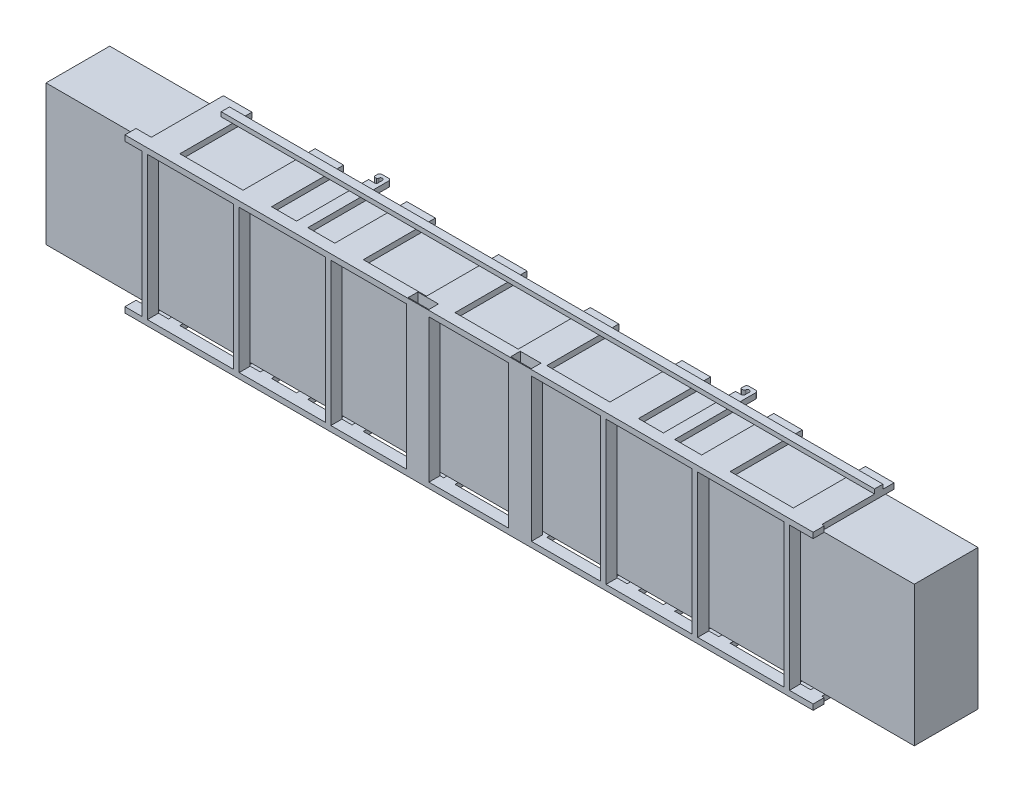
SolidWorks part; units mm, degrees
ref_plane "Front Plane" through (0, 0, 0) normal (0, 0, 1) x (1, 0, 0)
ref_plane "Top Plane" through (0, 0, 0) normal (0, 1, 0) x (1, 0, 0)
ref_plane "Right Plane" through (0, 0, 0) normal (1, 0, 0) x (0, 0, -1)
sketch "Sketch1" plane through (0, 0, 0) normal (0, 0, 1) x (1, 0, 0)
  line L0 (0, 1388) -> (6190, 1388)
  line L1 (0, 50) -> (6190, 50)
  line L2 (0, 50) -> (0, 0)
  line L3 (0, 0) -> (6190, 0)
  line L4 (6190, 50) -> (6190, 0)
  line L5 (0, 1388) -> (0, 1338)
  line L6 (0, 1338) -> (6190, 1338)
  line L7 (6190, 1388) -> (6190, 1338)
  dimension "D1" = 1288
  dimension "D2" = 50
extrude "Boss-Extrude1" add sketch "Sketch1" along normal blind 100
sketch "Sketch2" plane through (0, 0, 0) normal (0, -1, 0) x (1, 0, 0)
  line L0 (0, 100) -> (6190, 100) construction
  line L1 (2534, 100) -> (2734, 100)
  line L2 (2534, 100) -> (2534, 0)
  line L3 (2534, 0) -> (2734, 0)
  line L4 (2734, 100) -> (2734, 0)
  line L5 (0, 0) -> (6190, 0) construction
  line L6 (0, 100) -> (0, 0) construction
  line L8 (3456, 100) -> (3656, 100)
  line L9 (3456, 100) -> (3456, 0)
  line L10 (3456, 0) -> (3656, 0)
  line L11 (3656, 100) -> (3656, 0)
  point P8 (0, 50)
  dimension "D1" = 200
  dimension "D2" = 2534
  dimension "D3" = 2534
  dimension "D4" = 200
extrude "Boss-Extrude2" add sketch "Sketch2" against normal up to surface (1388 mm away) up to face at (3095, 1388, 50)
sketch "Sketch3" plane through (0, 1388, 0) normal (0, 1, 0) x (1, 0, 0)
  line L2 (0, -100) -> (0, 0) construction
  line L3 (6190, -100) -> (6190, 0) construction
  line L12 (2541, -7) -> (2727, -7)
  line L13 (2727, -7) -> (2727, -93)
  line L14 (2541, -93) -> (2727, -93)
  line L15 (2541, -7) -> (2541, -93)
  line L16 (3463, -7) -> (3649, -7)
  line L17 (3649, -7) -> (3649, -93)
  line L18 (3463, -93) -> (3649, -93)
  line L19 (3463, -7) -> (3463, -93)
  point P2 (6190, -50)
  dimension "D1" = 186
  dimension "D2" = 186
  dimension "D3" = 2541
  dimension "D4" = 2541
extrude "Cut-Extrude1" cut sketch "Sketch3" against normal through all
sketch "Sketch4" plane through (0, 50, 0) normal (0, 1, 0) x (1, 0, 0)
  line L0 (2534, 0) -> (0, 0) construction
  line L1 (152, 0) -> (202, 0)
  line L2 (152, 0) -> (152, -100)
  line L3 (152, -100) -> (202, -100)
  line L4 (202, 0) -> (202, -100)
  line L5 (2534, -100) -> (0, -100) construction
  line L6 (0, -100) -> (0, 0) construction
  line L7 (977, 0) -> (977, -100)
  line L8 (977, 0) -> (1027, 0)
  line L9 (1027, 0) -> (1027, -100)
  line L10 (977, -100) -> (1027, -100)
  line L11 (1802, 0) -> (1802, -100)
  line L12 (1802, 0) -> (1852, 0)
  line L13 (1852, 0) -> (1852, -100)
  line L14 (1802, -100) -> (1852, -100)
  line L15 (2627, 0) -> (2627, -100)
  line L16 (2627, 0) -> (2677, 0)
  line L17 (2677, 0) -> (2677, -100)
  line L18 (2627, -100) -> (2677, -100)
  line L19 (3452, 0) -> (3452, -100)
  line L20 (3452, 0) -> (3502, 0)
  line L21 (3502, 0) -> (3502, -100)
  line L22 (3452, -100) -> (3502, -100)
  line L23 (4277, 0) -> (4277, -100)
  line L24 (4277, 0) -> (4327, 0)
  line L25 (4327, 0) -> (4327, -100)
  line L26 (4277, -100) -> (4327, -100)
  line L27 (5102, 0) -> (5102, -100)
  line L28 (5102, 0) -> (5152, 0)
  line L29 (5152, 0) -> (5152, -100)
  line L30 (5102, -100) -> (5152, -100)
  line L31 (5927, 0) -> (5927, -100)
  line L32 (5927, 0) -> (5977, 0)
  line L33 (5977, 0) -> (5977, -100)
  line L34 (5927, -100) -> (5977, -100)
  dimension "D1" = 152
  dimension "D2" = 50
  dimension "D3" = 8
extrude "Boss-Extrude3" add sketch "Sketch4" along normal up to next
sketch "Sketch5" plane through (0, 0, 0) normal (0, 0, 1) x (1, 0, 0)
  line L0 (137.4, 1388) -> (137.4, 1338)
  line L1 (140.4, 1385.8) -> (140.4, 1338)
  line L2 (292.4, 1385.8) -> (140.4, 1385.8)
  line L3 (394, 1388) -> (394, 1338)
  line L4 (137.4, 1388) -> (394, 1388)
  line L5 (394, 1338) -> (292.4, 1338)
  line L6 (140.4, 1338) -> (137.4, 1338)
  line L7 (292.4, 1385.8) -> (292.4, 1338)
  line L8 (152, 1338) -> (137.4, 1338) construction
  line L9 (0, 1338) -> (152, 1338) construction
  line L10 (962.4, 1388) -> (962.4, 1338)
  line L11 (965.4, 1385.8) -> (965.4, 1338)
  line L12 (1117.4, 1385.8) -> (965.4, 1385.8)
  line L13 (1219, 1388) -> (1219, 1338)
  line L14 (962.4, 1388) -> (1219, 1388)
  line L15 (1219, 1338) -> (1117.4, 1338)
  line L16 (965.4, 1338) -> (962.4, 1338)
  line L17 (1117.4, 1385.8) -> (1117.4, 1338)
  line L18 (977, 1338) -> (962.4, 1338) construction
  line L19 (1787.4, 1388) -> (1787.4, 1338)
  line L20 (1790.4, 1385.8) -> (1790.4, 1338)
  line L21 (1942.4, 1385.8) -> (1790.4, 1385.8)
  line L22 (2044, 1388) -> (2044, 1338)
  line L23 (1787.4, 1388) -> (2044, 1388)
  line L24 (2044, 1338) -> (1942.4, 1338)
  line L25 (1790.4, 1338) -> (1787.4, 1338)
  line L26 (1942.4, 1385.8) -> (1942.4, 1338)
  line L27 (1802, 1338) -> (1787.4, 1338) construction
  line L28 (2612.4, 1388) -> (2612.4, 1338)
  line L29 (2615.4, 1385.8) -> (2615.4, 1338)
  line L30 (2767.4, 1385.8) -> (2615.4, 1385.8)
  line L31 (2869, 1388) -> (2869, 1338)
  line L32 (2612.4, 1388) -> (2869, 1388)
  line L33 (2869, 1338) -> (2767.4, 1338)
  line L34 (2615.4, 1338) -> (2612.4, 1338)
  line L35 (2767.4, 1385.8) -> (2767.4, 1338)
  line L36 (2627, 1338) -> (2612.4, 1338) construction
  line L37 (3437.4, 1388) -> (3437.4, 1338)
  line L38 (3440.4, 1385.8) -> (3440.4, 1338)
  line L39 (3592.4, 1385.8) -> (3440.4, 1385.8)
  line L40 (3694, 1388) -> (3694, 1338)
  line L41 (3437.4, 1388) -> (3694, 1388)
  line L42 (3694, 1338) -> (3592.4, 1338)
  line L43 (3440.4, 1338) -> (3437.4, 1338)
  line L44 (3592.4, 1385.8) -> (3592.4, 1338)
  line L45 (3452, 1338) -> (3437.4, 1338) construction
  line L46 (4262.4, 1388) -> (4262.4, 1338)
  line L47 (4265.4, 1385.8) -> (4265.4, 1338)
  line L48 (4417.4, 1385.8) -> (4265.4, 1385.8)
  line L49 (4519, 1388) -> (4519, 1338)
  line L50 (4262.4, 1388) -> (4519, 1388)
  line L51 (4519, 1338) -> (4417.4, 1338)
  line L52 (4265.4, 1338) -> (4262.4, 1338)
  line L53 (4417.4, 1385.8) -> (4417.4, 1338)
  line L54 (4277, 1338) -> (4262.4, 1338) construction
  line L55 (5087.4, 1388) -> (5087.4, 1338)
  line L56 (5090.4, 1385.8) -> (5090.4, 1338)
  line L57 (5242.4, 1385.8) -> (5090.4, 1385.8)
  line L58 (5344, 1388) -> (5344, 1338)
  line L59 (5087.4, 1388) -> (5344, 1388)
  line L60 (5344, 1338) -> (5242.4, 1338)
  line L61 (5090.4, 1338) -> (5087.4, 1338)
  line L62 (5242.4, 1385.8) -> (5242.4, 1338)
  line L63 (5102, 1338) -> (5087.4, 1338) construction
  line L64 (5912.4, 1388) -> (5912.4, 1338)
  line L65 (5915.4, 1385.8) -> (5915.4, 1338)
  line L66 (6067.4, 1385.8) -> (5915.4, 1385.8)
  line L67 (6169, 1388) -> (6169, 1338)
  line L68 (5912.4, 1388) -> (6169, 1388)
  line L69 (6169, 1338) -> (6067.4, 1338)
  line L70 (5915.4, 1338) -> (5912.4, 1338)
  line L71 (6067.4, 1385.8) -> (6067.4, 1338)
  line L72 (5927, 1338) -> (5912.4, 1338) construction
  line L73 (152, 694) -> (5977, 694) construction
  line L74 (152, 1338) -> (152, 50) construction
  line L75 (5977, 1338) -> (5977, 50) construction
  line L76 (5927, 50) -> (5912.4, 50) construction
  line L77 (5102, 50) -> (5087.4, 50) construction
  line L78 (4277, 50) -> (4262.4, 50) construction
  line L79 (3452, 50) -> (3437.4, 50) construction
  line L80 (2627, 50) -> (2612.4, 50) construction
  line L81 (1802, 50) -> (1787.4, 50) construction
  line L82 (977, 50) -> (962.4, 50) construction
  line L83 (152, 50) -> (137.4, 50) construction
  line L84 (6067.4, 2.2) -> (6067.4, 50)
  line L85 (5915.4, 50) -> (5912.4, 50)
  line L86 (6169, 50) -> (6067.4, 50)
  line L87 (5912.4, 0) -> (6169, 0)
  line L88 (6169, 0) -> (6169, 50)
  line L89 (6067.4, 2.2) -> (5915.4, 2.2)
  line L90 (5915.4, 2.2) -> (5915.4, 50)
  line L91 (5912.4, 0) -> (5912.4, 50)
  line L92 (5242.4, 2.2) -> (5242.4, 50)
  line L93 (5090.4, 50) -> (5087.4, 50)
  line L94 (5344, 50) -> (5242.4, 50)
  line L95 (5087.4, 0) -> (5344, 0)
  line L96 (5344, 0) -> (5344, 50)
  line L97 (5242.4, 2.2) -> (5090.4, 2.2)
  line L98 (5090.4, 2.2) -> (5090.4, 50)
  line L99 (5087.4, 0) -> (5087.4, 50)
  line L100 (4417.4, 2.2) -> (4417.4, 50)
  line L101 (4265.4, 50) -> (4262.4, 50)
  line L102 (4519, 50) -> (4417.4, 50)
  line L103 (4262.4, 0) -> (4519, 0)
  line L104 (4519, 0) -> (4519, 50)
  line L105 (4417.4, 2.2) -> (4265.4, 2.2)
  line L106 (4265.4, 2.2) -> (4265.4, 50)
  line L107 (4262.4, 0) -> (4262.4, 50)
  line L108 (3592.4, 2.2) -> (3592.4, 50)
  line L109 (3440.4, 50) -> (3437.4, 50)
  line L110 (3694, 50) -> (3592.4, 50)
  line L111 (3437.4, 0) -> (3694, 0)
  line L112 (3694, 0) -> (3694, 50)
  line L113 (3592.4, 2.2) -> (3440.4, 2.2)
  line L114 (3440.4, 2.2) -> (3440.4, 50)
  line L115 (3437.4, 0) -> (3437.4, 50)
  line L116 (2767.4, 2.2) -> (2767.4, 50)
  line L117 (2615.4, 50) -> (2612.4, 50)
  line L118 (2869, 50) -> (2767.4, 50)
  line L119 (2612.4, 0) -> (2869, 0)
  line L120 (2869, 0) -> (2869, 50)
  line L121 (2767.4, 2.2) -> (2615.4, 2.2)
  line L122 (2615.4, 2.2) -> (2615.4, 50)
  line L123 (2612.4, 0) -> (2612.4, 50)
  line L124 (1942.4, 2.2) -> (1942.4, 50)
  line L125 (1790.4, 50) -> (1787.4, 50)
  line L126 (2044, 50) -> (1942.4, 50)
  line L127 (1787.4, 0) -> (2044, 0)
  line L128 (2044, 0) -> (2044, 50)
  line L129 (1942.4, 2.2) -> (1790.4, 2.2)
  line L130 (1790.4, 2.2) -> (1790.4, 50)
  line L131 (1787.4, 0) -> (1787.4, 50)
  line L132 (1117.4, 2.2) -> (1117.4, 50)
  line L133 (965.4, 50) -> (962.4, 50)
  line L134 (1219, 50) -> (1117.4, 50)
  line L135 (962.4, 0) -> (1219, 0)
  line L136 (1219, 0) -> (1219, 50)
  line L137 (1117.4, 2.2) -> (965.4, 2.2)
  line L138 (965.4, 2.2) -> (965.4, 50)
  line L139 (962.4, 0) -> (962.4, 50)
  line L140 (292.4, 2.2) -> (292.4, 50)
  line L141 (140.4, 50) -> (137.4, 50)
  line L142 (394, 50) -> (292.4, 50)
  line L143 (137.4, 0) -> (394, 0)
  line L144 (394, 0) -> (394, 50)
  line L145 (292.4, 2.2) -> (140.4, 2.2)
  line L146 (140.4, 2.2) -> (140.4, 50)
  line L147 (137.4, 0) -> (137.4, 50)
  dimension "D1" = 50
  dimension "D2" = 50
  dimension "D3" = 8
extrude "Boss-Extrude4" add sketch "Sketch5" against normal blind 648.4
sketch "Sketch8" plane through (0, 50, 0) normal (0, 1, 0) x (1, 0, 0)
  line L0 (1443.4, 648.4) -> (1497.5, 648.4)
  line L1 (1453.4, 693.4) -> (1467.5, 693.4)
  line L2 (1443.4, 728.4) -> (1443.4, 703.4)
  line L3 (1512.5, 703.4) -> (1512.5, 663.4)
  line L4 (1545, 0) -> (1443.4, 0)
  line L5 (1443.4, 0) -> (1443.4, 648.4)
  line L6 (1545, 0) -> (1545, 728.4)
  line L7 (1463.4, 748.4) -> (1525, 748.4)
  line L8 (0, 0) -> (1443.4, 0) construction
  line L9 (6190, 0) -> (4845, 0) construction
  line L10 (4845, 0) -> (4743.4, 0)
  line L11 (4812.5, 703.4) -> (4812.5, 663.4)
  line L12 (4743.4, 728.4) -> (4743.4, 703.4)
  line L13 (4753.4, 693.4) -> (4767.5, 693.4)
  line L14 (4743.4, 0) -> (4743.4, 648.4)
  line L15 (4845, 0) -> (4845, 728.4)
  line L16 (4743.4, 648.4) -> (4797.5, 648.4)
  line L17 (4763.4, 748.4) -> (4825, 748.4)
  arc A0 (1497.5, 648.4) -> (1512.5, 663.4) centre (1497.5, 663.4) ccw
  arc A1 (1443.4, 703.4) -> (1453.4, 693.4) centre (1453.4, 703.4) ccw
  arc A2 (1463.4, 748.4) -> (1443.4, 728.4) centre (1463.4, 728.4) ccw
  arc A3 (1545, 728.4) -> (1525, 748.4) centre (1525, 728.4) ccw
  arc A4 (1512.5, 703.4) -> (1477.5, 703.4) centre (1495, 703.4) ccw
  arc A5 (1467.5, 693.4) -> (1477.5, 703.4) centre (1467.5, 703.4) ccw
  arc A6 (4845, 728.4) -> (4825, 748.4) centre (4825, 728.4) ccw
  arc A7 (4763.4, 748.4) -> (4743.4, 728.4) centre (4763.4, 728.4) ccw
  arc A8 (4767.5, 693.4) -> (4777.5, 703.4) centre (4767.5, 703.4) ccw
  arc A9 (4743.4, 703.4) -> (4753.4, 693.4) centre (4753.4, 703.4) ccw
  arc A10 (4812.5, 703.4) -> (4777.5, 703.4) centre (4795, 703.4) ccw
  arc A11 (4797.5, 648.4) -> (4812.5, 663.4) centre (4797.5, 663.4) ccw
extrude "Boss-Extrude5" add sketch "Sketch8" against normal blind 50
sketch "Sketch9" plane through (0, 1388, 0) normal (0, 1, 0) x (1, 0, 0)
  line L0 (1443.4, 648.4) -> (1497.5, 648.4)
  line L1 (1453.4, 693.4) -> (1467.5, 693.4)
  line L2 (1443.4, 728.4) -> (1443.4, 703.4)
  line L3 (1512.5, 703.4) -> (1512.5, 663.4)
  line L4 (1545, 0) -> (1443.4, 0)
  line L5 (1443.4, 0) -> (1443.4, 648.4)
  line L6 (1545, 0) -> (1545, 728.4)
  line L7 (1463.4, 748.4) -> (1525, 748.4)
  line L8 (0, 0) -> (1443.4, 0) construction
  line L9 (6190, 0) -> (4845, 0) construction
  line L10 (4845, 0) -> (4743.4, 0)
  line L11 (4812.5, 703.4) -> (4812.5, 663.4)
  line L12 (4743.4, 728.4) -> (4743.4, 703.4)
  line L13 (4753.4, 693.4) -> (4767.5, 693.4)
  line L14 (4743.4, 0) -> (4743.4, 648.4)
  line L15 (4845, 0) -> (4845, 728.4)
  line L16 (4743.4, 648.4) -> (4797.5, 648.4)
  line L17 (4763.4, 748.4) -> (4825, 748.4)
  arc A0 (1497.5, 648.4) -> (1512.5, 663.4) centre (1497.5, 663.4) ccw
  arc A1 (1443.4, 703.4) -> (1453.4, 693.4) centre (1453.4, 703.4) ccw
  arc A2 (1463.4, 748.4) -> (1443.4, 728.4) centre (1463.4, 728.4) ccw
  arc A3 (1545, 728.4) -> (1525, 748.4) centre (1525, 728.4) ccw
  arc A4 (1512.5, 703.4) -> (1477.5, 703.4) centre (1495, 703.4) ccw
  arc A5 (1467.5, 693.4) -> (1477.5, 703.4) centre (1467.5, 703.4) ccw
  arc A6 (4845, 728.4) -> (4825, 748.4) centre (4825, 728.4) ccw
  arc A7 (4763.4, 748.4) -> (4743.4, 728.4) centre (4763.4, 728.4) ccw
  arc A8 (4767.5, 693.4) -> (4777.5, 703.4) centre (4767.5, 703.4) ccw
  arc A9 (4743.4, 703.4) -> (4753.4, 693.4) centre (4753.4, 703.4) ccw
  arc A10 (4812.5, 703.4) -> (4777.5, 703.4) centre (4795, 703.4) ccw
  arc A11 (4797.5, 648.4) -> (4812.5, 663.4) centre (4797.5, 663.4) ccw
extrude "Boss-Extrude6" add sketch "Sketch9" against normal blind 50
sketch "Sketch10" plane through (6169, 0, 0) normal (1, 0, 0) x (0, 0, -1)
  line L0 (648.4, 0) -> (0, 0) construction
  line L1 (548.4, 0) -> (473.4, 0)
  line L2 (548.4, 0) -> (548.4, -40)
  line L3 (548.4, -40) -> (473.4, -40)
  line L4 (473.4, 0) -> (473.4, -40)
  line L5 (648.4, 1388) -> (0, 1388) construction
  line L6 (548.4, 1388) -> (473.4, 1388)
  line L7 (548.4, 1388) -> (548.4, 1428)
  line L8 (548.4, 1428) -> (473.4, 1428)
  line L9 (473.4, 1388) -> (473.4, 1428)
  dimension "D1" = 100
  dimension "D2" = 75
  dimension "D3" = 75
  dimension "D4" = 100
extrude "Boss-Extrude7" add sketch "Sketch10" against normal up to surface (5876.6 mm away) up to face at (292.4, 1361.9, -324.2)
sketch "Sketch11" plane through (0, 0, 0) normal (1, 0, 0) x (0, 0, -1)
  line L1 (0, 1338) -> (572.9754, 1338)
  line L2 (0, 1338) -> (0, 78.6868)
  line L3 (0, 78.6868) -> (572.9754, 78.6868)
  line L4 (572.9754, 1338) -> (572.9754, 78.6868)
extrude "Boss-Extrude10" add sketch "Sketch11" along normal blind 7000 separate body
sketch "Sketch12" plane through (0, 0, 0) normal (-1, 0, 0) x (0, 0, 1)
  line L1 (-572.9754, 78.6868) -> (0, 78.6868)
  line L2 (-572.9754, 78.6868) -> (-572.9754, 1338)
  line L3 (-572.9754, 1338) -> (0, 1338)
  line L4 (0, 78.6868) -> (0, 1338)
extrude "Boss-Extrude11" add sketch "Sketch12" along normal blind 810
